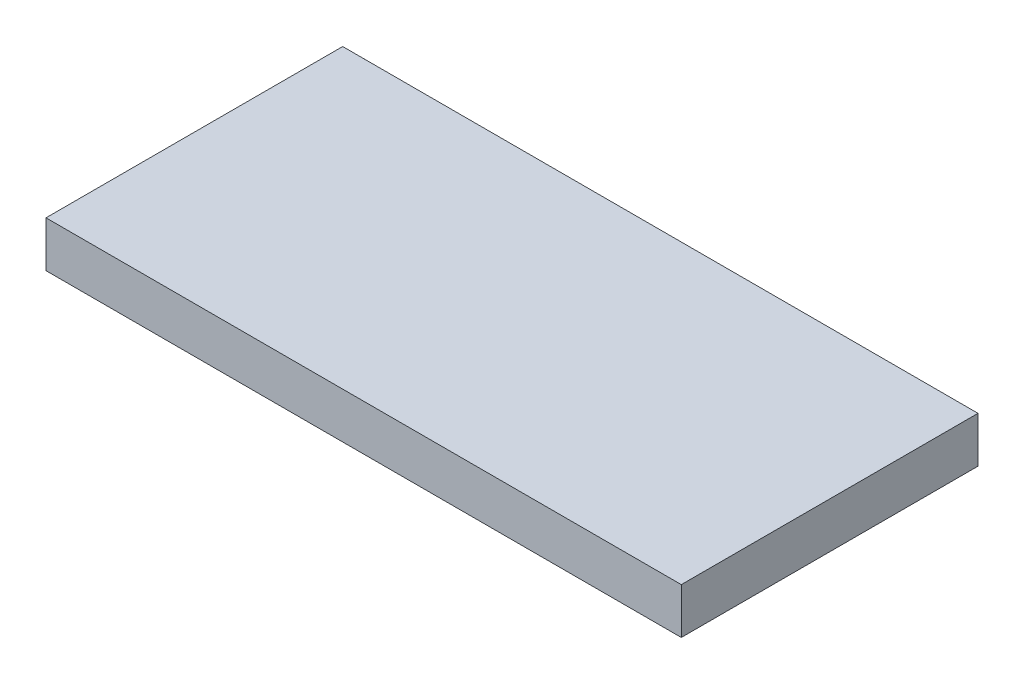
SolidWorks part; units mm, degrees
ref_plane "Front Plane" through (0, 0, 0) normal (0, 0, 1) x (1, 0, 0)
ref_plane "Top Plane" through (0, 0, 0) normal (0, 1, 0) x (1, 0, 0)
ref_plane "Right Plane" through (0, 0, 0) normal (1, 0, 0) x (0, 0, -1)
sketch "Sketch1" plane through (0, 0, 0) normal (0, 1, 0) x (1, 0, 0)
  line L1 (0, 0) -> (66.2458, 0)
  line L2 (0, 0) -> (0, 30.9372)
  line L3 (0, 30.9372) -> (66.2458, 30.9372)
  line L4 (66.2458, 0) -> (66.2458, 30.9372)
  dimension "D1" = 30.9372
extrude "Extrude1" add sketch "Sketch1" against normal blind 4.7752
